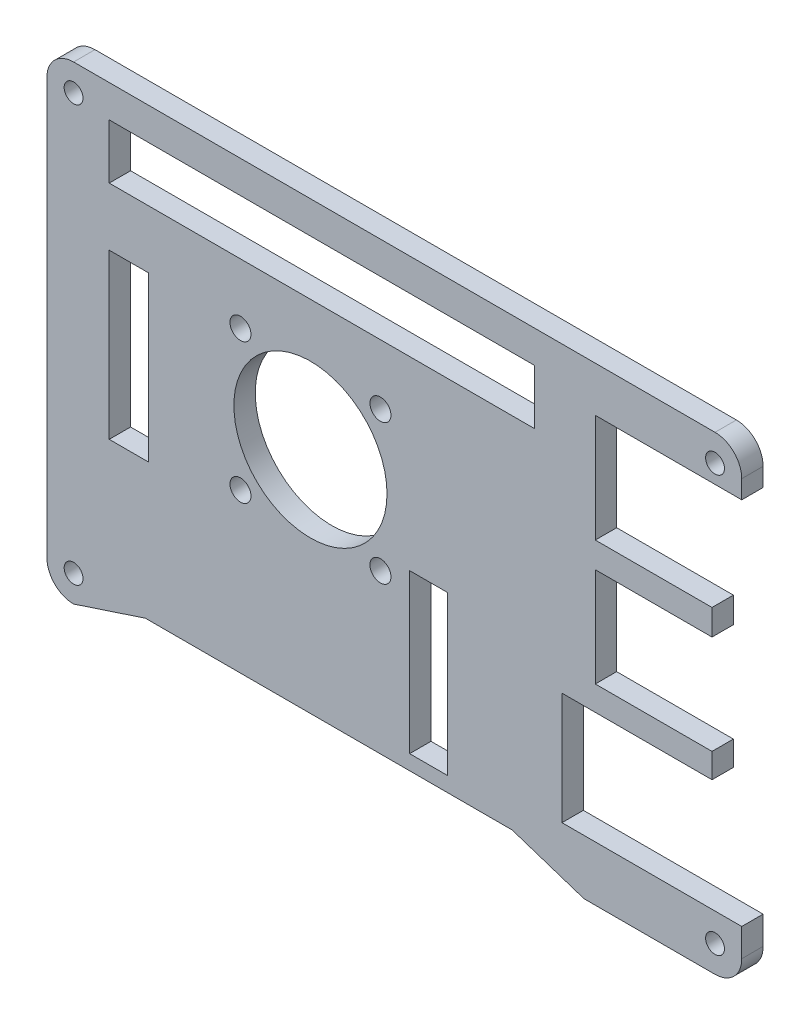
SolidWorks part; units mm, degrees
ref_plane "Front Plane" through (0, 0, 0) normal (0, 0, 1) x (1, 0, 0)
ref_plane "Top Plane" through (0, 0, 0) normal (0, 1, 0) x (1, 0, 0)
ref_plane "Right Plane" through (0, 0, 0) normal (1, 0, 0) x (0, 0, -1)
sketch "Sketch1" plane through (0, 0, 0) normal (0, 0, 1) x (1, 0, 0)
  line L0 (40.325, 24.0683) -> (61.2149, 24.0683) construction
  line L1 (61.2149, 24.0683) -> (61.2149, 26.6839) construction
  line L2 (57.4049, 30.5077) -> (-34.0849, 30.5077) construction
  line L3 (40.325, 8.6582) -> (40.325, 24.0683) construction
  line L4 (56.975, 8.6582) -> (40.325, 8.6582) construction
  line L5 (56.975, 4.9979) -> (56.975, 8.6582) construction
  line L6 (40.325, 4.9979) -> (56.975, 4.9979) construction
  line L7 (40.325, -9.1218) -> (40.325, 4.9979) construction
  line L8 (56.975, -9.1218) -> (40.325, -9.1218) construction
  line L9 (56.975, -12.628) -> (56.975, -9.1218) construction
  line L10 (35.575, -12.628) -> (56.975, -12.628) construction
  line L11 (35.575, -28.6278) -> (35.575, -12.628) construction
  line L12 (61.2149, -28.6278) -> (35.575, -28.6278) construction
  line L13 (61.2149, -32.6134) -> (61.2149, -28.6278) construction
  line L14 (38.7143, -36.451) -> (57.405, -36.451) construction
  line L15 (28.4743, -33.0844) -> (38.7143, -36.451) construction
  line L16 (-23.8449, -33.0844) -> (28.4743, -33.0844) construction
  line L17 (-34.0849, -36.451) -> (-23.8449, -33.0844) construction
  line L18 (-37.8949, 26.6977) -> (-37.8949, -32.641) construction
  line L19 (40.325, 24.0683) -> (61.2149, 24.0683)
  line L20 (61.2149, 24.0683) -> (61.2149, 26.6839)
  line L21 (57.4049, 30.5077) -> (-34.0849, 30.5077)
  line L22 (40.325, 8.6582) -> (40.325, 24.0683)
  line L23 (56.975, 8.6582) -> (40.325, 8.6582)
  line L24 (56.975, 4.9979) -> (56.975, 8.6582)
  line L25 (40.325, 4.9979) -> (56.975, 4.9979)
  line L26 (40.325, -9.1218) -> (40.325, 4.9979)
  line L27 (56.975, -9.1218) -> (40.325, -9.1218)
  line L28 (56.975, -12.628) -> (56.975, -9.1218)
  line L29 (35.575, -12.628) -> (56.975, -12.628)
  line L30 (35.575, -28.6278) -> (35.575, -12.628)
  line L31 (61.2149, -28.6278) -> (35.575, -28.6278)
  line L32 (61.2149, -32.6134) -> (61.2149, -28.6278)
  line L33 (38.7143, -36.451) -> (57.405, -36.451)
  line L34 (28.4743, -33.0844) -> (38.7143, -36.451)
  line L35 (-23.8449, -33.0844) -> (28.4743, -33.0844)
  line L36 (-34.0849, -36.451) -> (-23.8449, -33.0844)
  line L37 (-37.8949, 26.6977) -> (-37.8949, -32.641)
  line L38 (-23.4169, -23.6989) -> (-23.4169, 9.8012) construction
  line L39 (-29.0049, 25.897) -> (31.6883, 25.897)
  line L40 (-29.0049, 25.897) -> (-29.0049, 18.087)
  line L41 (-29.0049, 18.087) -> (31.6883, 18.087)
  line L42 (31.6883, 25.897) -> (31.6883, 18.087)
  line L43 (-29.0049, 9.8012) -> (-23.4169, 9.8012)
  line L44 (-29.0049, 9.8012) -> (-29.0049, -13.5668)
  line L45 (-29.0049, -13.5668) -> (-23.4169, -13.5668)
  line L46 (-23.4169, 9.8012) -> (-23.4169, -13.5668)
  line L47 (-29.0049, 9.2932) -> (-23.4169, 9.2932)
  line L50 (13.845, -8.3602) -> (19.2484, -8.3602)
  line L51 (13.845, -8.3602) -> (13.845, -30.9668)
  line L52 (13.845, -30.9668) -> (19.2484, -30.9668)
  line L53 (19.2484, -8.3602) -> (19.2484, -30.9668)
  arc A0 (61.2149, 26.6839) -> (57.4049, 30.5077) centre (57.4049, 26.6977) ccw construction
  circle A1 centre (57.4049, 26.6977) radius 1.3462 construction
  arc A2 (57.405, -36.451) -> (61.2149, -32.6134) centre (57.405, -32.641) ccw construction
  arc A3 (-37.8949, -32.641) -> (-34.0849, -36.451) centre (-34.0849, -32.641) ccw construction
  arc A4 (-34.0849, 30.5077) -> (-37.8949, 26.6977) centre (-34.0849, 26.6977) ccw construction
  circle A5 centre (-34.0849, 26.6977) radius 1.3462 construction
  circle A6 centre (-34.0849, -32.641) radius 1.3462 construction
  arc A7 (61.2149, 26.6839) -> (57.4049, 30.5077) centre (57.4049, 26.6977) ccw
  circle A8 centre (57.4049, 26.6977) radius 1.3462
  arc A9 (57.405, -36.451) -> (61.2149, -32.6134) centre (57.405, -32.641) ccw
  arc A10 (-37.8949, -32.641) -> (-34.0849, -36.451) centre (-34.0849, -32.641) ccw
  arc A11 (-34.0849, 30.5077) -> (-37.8949, 26.6977) centre (-34.0849, 26.6977) ccw
  circle A12 centre (-34.0849, 26.6977) radius 1.3462
  circle A13 centre (-34.0849, -32.641) radius 1.3462
  circle A14 centre (57.405, -32.641) radius 1.3462 construction
  circle A15 centre (57.405, -32.641) radius 1.3462
  dimension "D1" = 23.368
  dimension "D2" = 0.508
extrude "Boss-Extrude1" add sketch "Sketch1" along normal blind 3.048 contours L21 A11 L37 A10 L36 L35 L34 L33 A9 L32 L31 L30 L29 L28 L27 L26 L25 L24 L23 L22 L19 L20 A7 A15 A13 A12 L50 L53 L52 L51 L39 L42 L41 L40 L43 L46 L45 L44 A8
sketch "Sketch2" plane through (0, 0, 3.048) normal (0, 0, 1) x (1, 0, 0)
  line L2 (-37.8949, 26.6977) -> (-37.8949, -32.641) construction
  line L5 (57.4049, 30.5077) -> (-34.0849, 30.5077) construction
  line L6 (-10.2851, -8.9639) -> (-10.2851, 8.0033) construction
  line L7 (-8.7865, -10.4625) -> (8.1807, -10.4625) construction
  line L8 (9.6793, -8.9639) -> (9.6793, 8.0033) construction
  line L9 (8.1807, 9.5019) -> (-8.7865, 9.5019) construction
  line L10 (-10.2851, -10.4625) -> (9.6793, 9.5019) construction
  circle A0 centre (-0.3029, -0.4803) radius 10.922
  circle A1 centre (-10.2851, -10.4625) radius 1.4986
  circle A2 centre (-10.2851, 9.5019) radius 1.4986
  circle A3 centre (9.6793, -10.4625) radius 1.4986
  circle A4 centre (9.6793, 9.5019) radius 1.4986
  dimension "D1" = 26.67
  dimension "D2" = 20.066
  dimension "D3" = 21.844
  dimension "D4" = 16.9672
  dimension "D5" = 2.9972
extrude "Cut-Extrude1" cut sketch "Sketch2" against normal through all
sketch "Sketch3" [suppressed] plane through (0, 0, 3.048) normal (0, 0, 1) x (1, 0, 0)
  line L0 (13.845, -30.9668) -> (19.2484, -30.9668) construction
  line L1 (-29.0049, 25.897) -> (31.6883, 25.897)
  line L2 (-29.0049, 25.897) -> (-29.0049, -30.9668)
  line L3 (-29.0049, -30.9668) -> (31.6883, -30.9668)
  line L4 (31.6883, 25.897) -> (31.6883, -30.9668)
  line L5 (31.6883, 25.897) -> (31.6883, 18.087) construction
extrude "Boss-Extrude2" [suppressed] add sketch "Sketch3" against normal up to vertex
